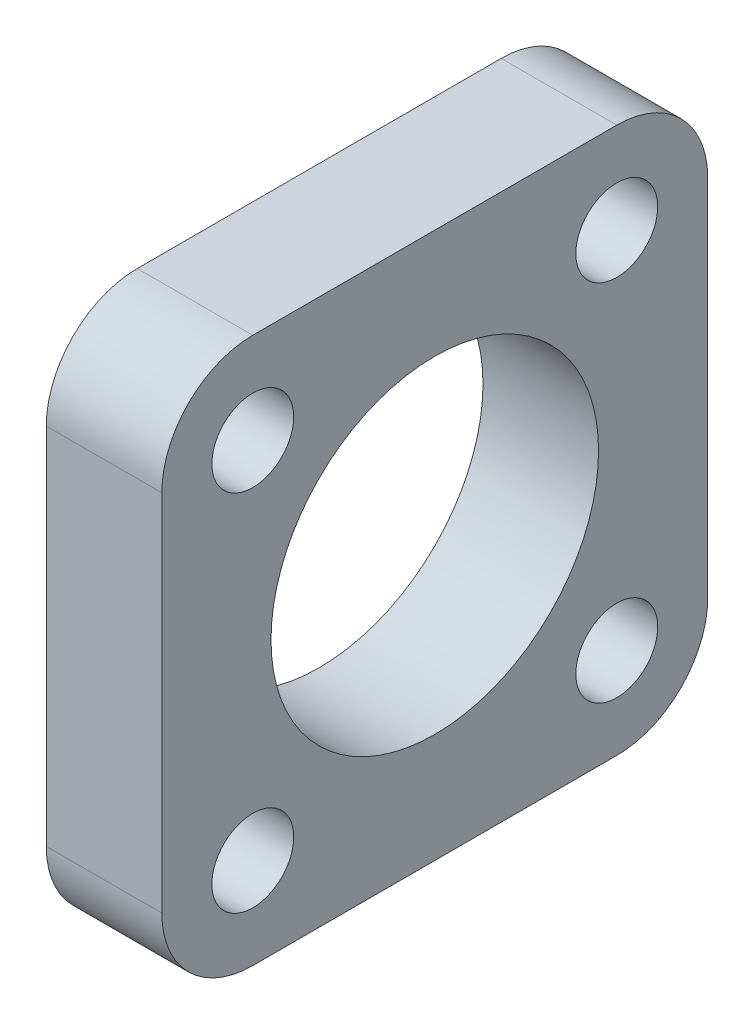
SolidWorks part; units mm, degrees
ref_plane "Alzado" through (0, 0, 0) normal (0, 0, 1) x (1, 0, 0)
ref_plane "Planta" through (0, 0, 0) normal (0, 1, 0) x (1, 0, 0)
ref_plane "Vista lateral" through (0, 0, 0) normal (1, 0, 0) x (0, 0, -1)
sketch "Croquis1" plane through (0, 0, 0) normal (1, 0, 0) x (0, 0, -1)
  line L1 (-15, -15) -> (15, -15)
  line L2 (-15, -15) -> (-15, 15)
  line L3 (-15, 15) -> (15, 15)
  line L4 (15, -15) -> (15, 15)
  line L5 (-15, -15) -> (15, 15) construction
  line L6 (-15, 15) -> (15, -15) construction
  circle A0 centre (0, 0) radius 9
  dimension "D1" = 30
  dimension "18" = 18
extrude "Saliente-Extruir1" add sketch "Croquis1" along normal mid plane 6.35
hole_wizard "Taladro de margen para M41" positions "Croquis2" profile "Croquis3" hole size "M4" standard "Ansi Metric" end condition up to next
sketch "Croquis2" plane through (3.175, 0, 0) normal (1, 0, 0) x (0, 0, -1)
  line L8 (-10, 10) -> (-10, -10) construction
  line L9 (-10, -10) -> (10, -10) construction
  line L10 (10, -10) -> (10, 10) construction
  line L11 (10, 10) -> (-10, 10) construction
  point P74 (-10, 10)
  point P75 (-10, -10)
  point P76 (10, -10)
  point P78 (10, 10)
  point P83 (0, 10)
  point P85 (10, 0)
  dimension "25" = 20
sketch "Croquis3" plane through (3.175, 10, 10) normal (0, 1, 0) x (0, 0, -1)
  line L0 (0, 0) -> (0, 6.35)
  line L1 (0, 6.35) -> (2.25, 6.35)
  line L2 (2.25, 6.35) -> (2.25, 0)
  line L5 (2.25, 0) -> (0, 0)
  line L11 (0, -6.35) -> (0, 107.95) construction
  dimension "Diámetro de taladro hasta el siguiente" = 4.5
  dimension "Profundidad de taladro hasta el siguiente" = 6.35
fillet "Redondeo1" radius 5 4 edges at (0, -15, -15) (0, -15, 15) (0, 15, -15) (0, 15, 15)
